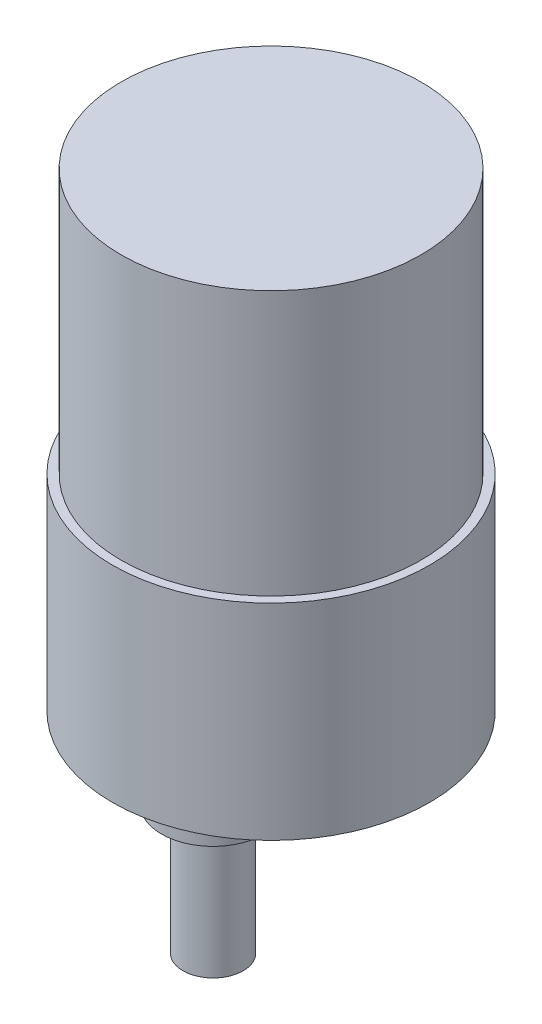
SolidWorks part; units mm, degrees
ref_plane "Alzado" through (0, 0, 0) normal (0, 0, 1) x (1, 0, 0)
ref_plane "Planta" through (0, 0, 0) normal (0, 1, 0) x (1, 0, 0)
ref_plane "Vista lateral" through (0, 0, 0) normal (1, 0, 0) x (0, 0, -1)
sketch "Croquis1" plane through (0, 0, 0) normal (0, 1, 0) x (1, 0, 0)
  line L0 (0, 41.1552) -> (0, -34.8404) construction
  line L1 (-46.3813, 0) -> (49.6476, 0) construction
  circle A0 centre (0, 0) radius 18.4
  dimension "D1" = 36.8
extrude "Saliente-Extruir1" add sketch "Croquis1" against normal blind 54.56
sketch "Croquis2" plane through (0, -54.56, 0) normal (0, -1, 0) x (1, 0, 0)
  line L0 (0, 19.5094) -> (0, -19.9637) construction
  line L1 (-22.8426, 0) -> (24.1825, 0) construction
  line L2 (0, 18.4) -> (17.8762, 18.4) construction
  line L3 (-7.2714, 12.73) -> (14.5284, 12.73) construction
  circle A0 centre (0, 6.73) radius 6
  circle A1 centre (0, 0) radius 18.4 construction
  point P11 (0, 9.7774)
  dimension "D1" = 5.67
  dimension "D2" = 12
extrude "Saliente-Extruir2" add sketch "Croquis2" along normal blind 6
sketch "Croquis3" plane through (0, -60.56, 0) normal (0, -1, 0) x (1, 0, 0)
  line L0 (0, 17.7619) -> (0, -10.8323) construction
  line L1 (-22.4612, 6.73) -> (25.9658, 6.73) construction
  circle A0 centre (0, 6.73) radius 3.5
  dimension "D1" = 7
extrude "Saliente-Extruir3" add sketch "Croquis3" along normal blind 15
sketch "Croquis4" plane through (0, -75.56, 0) normal (0, -1, 0) x (-1, 0, 0)
  line L0 (0, -17.6659) -> (0, 17.1905) construction
  line L1 (12.7543, -6.73) -> (-24.241, -6.73) construction
  line L2 (0, -3.23) -> (-8.3017, -3.23) construction
  line L3 (2.4495, -4.23) -> (-2.4495, -4.23)
  circle A0 centre (0, -6.73) radius 3.5 construction
  circle A1 centre (0, -6.73) radius 3.5 construction
  arc A2 (2.4495, -4.23) -> (-2.4495, -4.23) centre (0, -6.73) ccw
  dimension "D1" = 1
extrude "Cortar-Extruir1" cut sketch "Croquis4" against normal blind 15
sketch "Croquis5" plane through (0, 0, 0) normal (0, 1, 0) x (1, 0, 0)
  line L0 (0, 26.3778) -> (0, -33.2157) construction
  line L1 (-30.9571, 0) -> (29.4482, 0) construction
  circle A0 centre (0, 0) radius 17.4
  dimension "D1" = 34.8
sketch "Croquis6" plane through (0, 0, 0) normal (0, 1, 0) x (1, 0, 0)
  line L0 (0, 45.6206) -> (0, -45.6206) construction
  line L1 (0, 26.3778) -> (0, -33.2157) construction
  line L2 (-38.3423, -0.0285) -> (40.6821, -0.0285) construction
  circle A0 centre (0, 0) radius 18.4285
  point P8 (1.1162, 1.5711)
  point P9 (22.247, 1.1184)
  point P10 (0, 0)
  dimension "D1" = 36.8569
extrude "Cortar-Extruir2" cut sketch "Croquis6" against normal blind 30.7
sketch "Croquis7" plane through (0, -30.7, 0) normal (0, 1, 0) x (1, 0, 0)
  line L0 (0, 37.9347) -> (0, -35.1466) construction
  line L1 (-40.6493, 0) -> (45.703, 0) construction
  circle A0 centre (0, 0) radius 17.4
  dimension "D1" = 34.8
extrude "Saliente-Extruir5" add sketch "Croquis7" along normal blind 30.7
